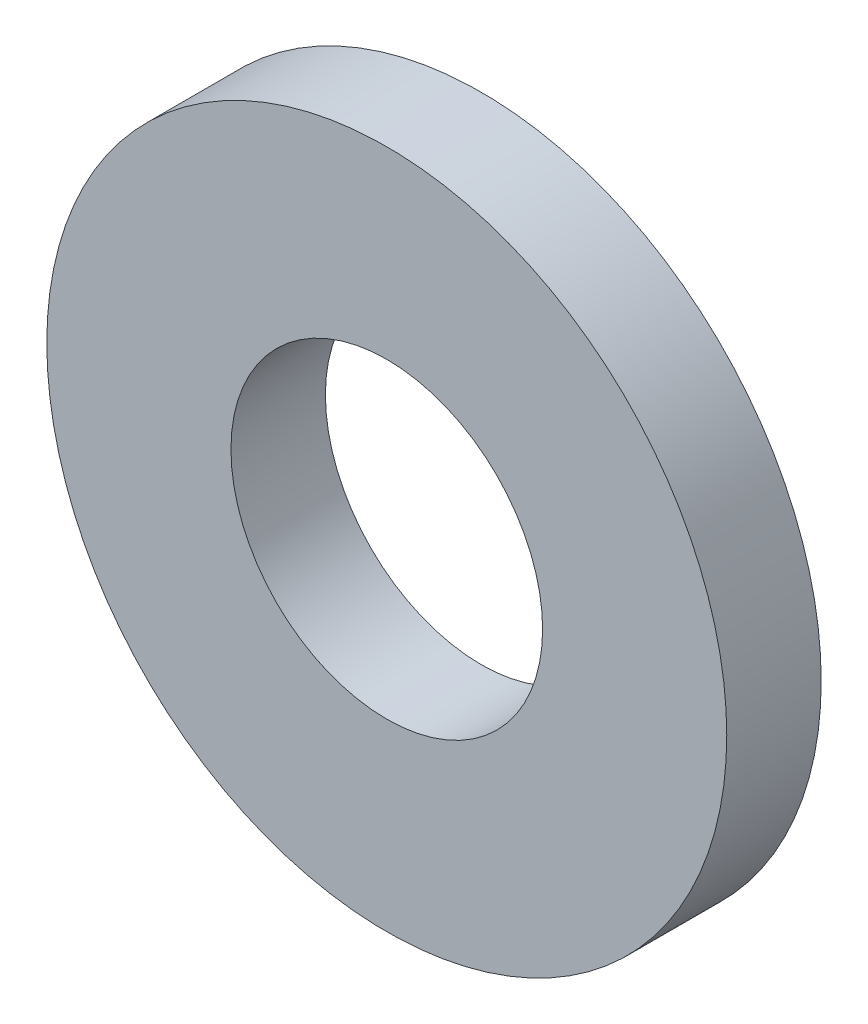
SolidWorks part; units mm, degrees
ref_plane "Front Plane" through (0, 0, 0) normal (0, 0, 1) x (1, 0, 0)
ref_plane "Top Plane" through (0, 0, 0) normal (0, 1, 0) x (1, 0, 0)
ref_plane "Right Plane" through (0, 0, 0) normal (1, 0, 0) x (0, 0, -1)
sketch "Sketch2" plane through (0, 0, 0) normal (0, 0, 1) x (1, 0, 0)
  circle A0 centre (0, 0) radius 1.65
  circle A1 centre (0, 0) radius 3.6
  dimension "D1" = 7.2
  dimension "D2" = 3.3
extrude "Boss-Extrude1" add sketch "Sketch2" along normal blind 1
